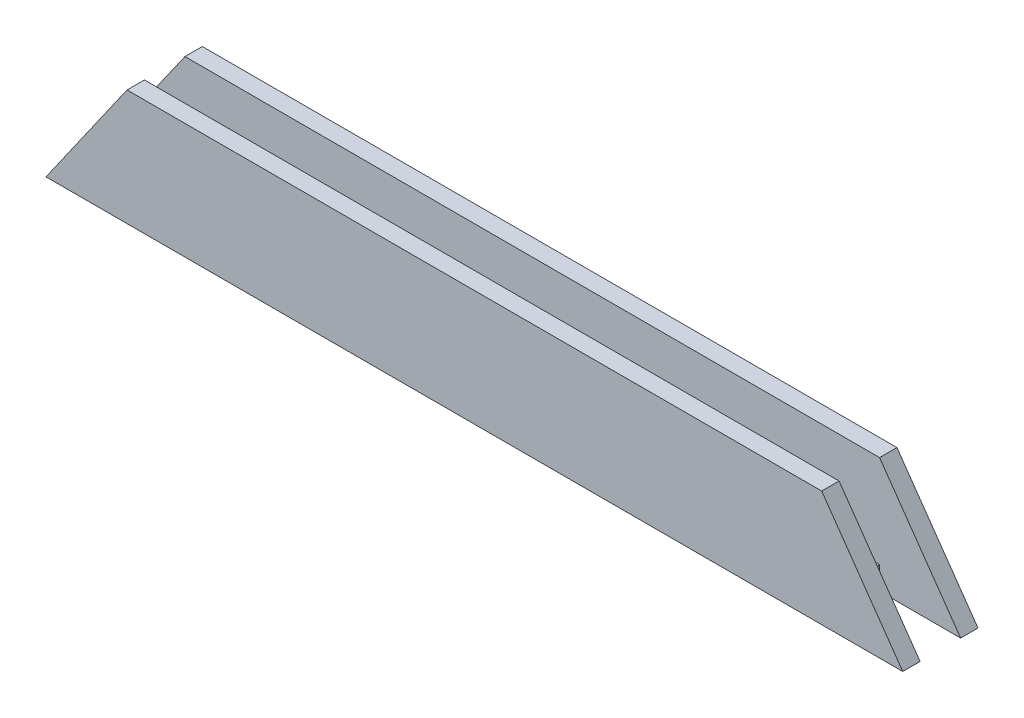
SolidWorks part; units mm, degrees
ref_plane "Front Plane" through (0, 0, 0) normal (0, 0, 1) x (1, 0, 0)
ref_plane "Top Plane" through (0, 0, 0) normal (0, 1, 0) x (1, 0, 0)
ref_plane "Right Plane" through (0, 0, 0) normal (1, 0, 0) x (0, 0, -1)
sketch "Sketch1" plane through (0, 0, 0) normal (0, 1, 0) x (1, 0, 0)
  line L1 (-37, -3.25) -> (37, -3.25)
  line L2 (-37, -3.25) -> (-37, 3.25)
  line L3 (-37, 3.25) -> (37, 3.25)
  line L4 (37, -3.25) -> (37, 3.25)
  line L5 (-37, -3.25) -> (37, 3.25) construction
  line L6 (-37, 3.25) -> (37, -3.25) construction
  point P0 (0, 0)
  dimension "D1" = 74
  dimension "D2" = 6.5
ref_plane "Plane1" through (0, 10, 0) normal (0, 1, 0) x (1, 0, 0)
sketch "Sketch2" plane through (0, 10, 0) normal (0, 1, 0) x (1, 0, 0)
  line L0 (-37, -3.25) -> (37, -3.25) construction
  line L1 (-30, 3.25) -> (30, 3.25)
  line L2 (-30, 3.25) -> (-30, -3.25)
  line L3 (-30, -3.25) -> (30, -3.25)
  line L4 (30, 3.25) -> (30, -3.25)
  line L5 (-30, 3.25) -> (30, -3.25) construction
  line L6 (-30, -3.25) -> (30, 3.25) construction
  point P0 (0, 0)
  dimension "D1" = 60
loft "Loft2" add profiles "Sketch2", "Sketch1"
shell "Shell1" thickness 1.5
sketch "Sketch3" plane through (0, 2, 0) normal (0, 1, 0) x (1, 0, 0)
  line L0 (-35.6, -1.75) -> (35.6, -1.75) construction
  line L1 (-37, -1.75) -> (-30, -1.75)
  line L2 (-37, -1.75) -> (-37, 1.75)
  line L3 (-37, 1.75) -> (-30, 1.75)
  line L4 (-30, -1.75) -> (-30, 1.75)
  line L5 (-37, -1.75) -> (-30, 1.75) construction
  line L6 (-37, 1.75) -> (-30, -1.75) construction
  line L7 (-37, 3.25) -> (-37, -3.25) construction
  point P0 (-33.5, 0)
extrude "Cut-Extrude1" cut sketch "Sketch3" against normal blind 10
mirror "Mirror1" about plane through (0, 0, 0) normal (1, 0, 0) of "Cut-Extrude1"
equation "\"D1@Sketch1\"=60mm+14mm"
